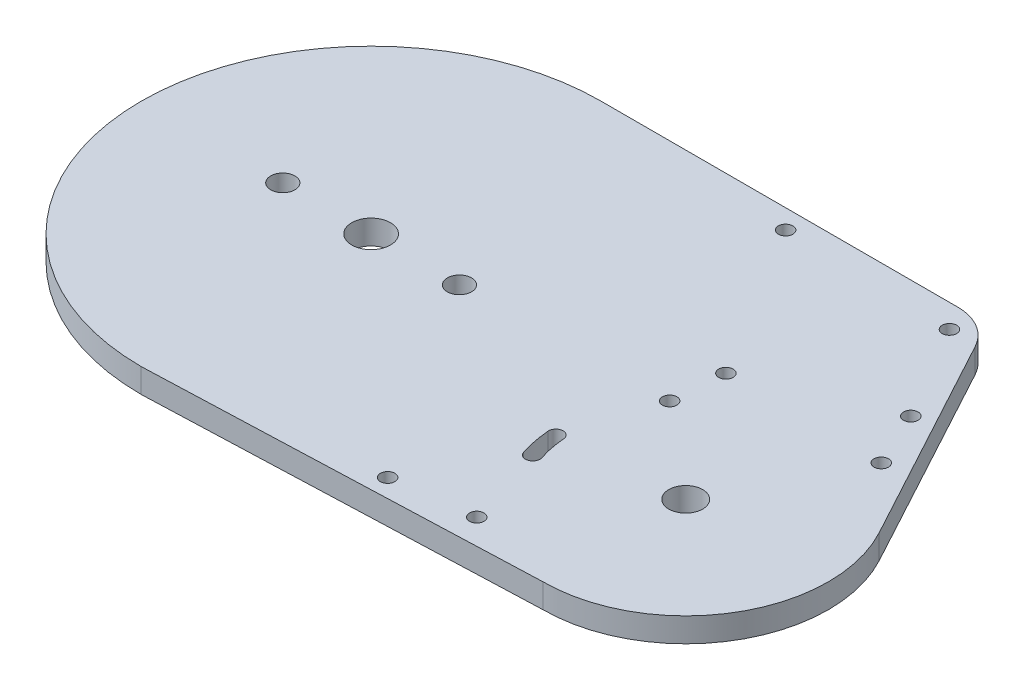
SolidWorks part; units mm, degrees
ref_plane "前视基准面" through (0, 0, 0) normal (0, 0, 1) x (1, 0, 0)
ref_plane "上视基准面" through (0, 0, 0) normal (0, 1, 0) x (1, 0, 0)
ref_plane "右视基准面" through (0, 0, 0) normal (1, 0, 0) x (0, 0, -1)
sketch "Sketch1" plane through (0, 0, 0) normal (0, 1, 0) x (1, 0, 0)
  line L0 (0, 0) -> (0, -15) construction
  line L1 (0, -15) -> (80, -15) construction
  line L2 (0, -47.5) -> (0, -44.5) construction
  line L3 (0, -44.5) -> (94.3585, -44.5) construction
  line L4 (0, -47.5) -> (80, -44.5)
  line L5 (0, 47.5) -> (73.764, 47.5)
  line L6 (82.559, 42.259) -> (105.9453, -0.9611)
  line L7 (0, 0) -> (80, -15) construction
  line L8 (80, -15) -> (60.7426, 0.9422) construction
  line L9 (78.1615, 44.8795) -> (78.8831, 46.0904) construction
  line L10 (78.8831, 46.0904) -> (76.8355, 42.6542) construction
  line L11 (73.764, 47.5) -> (82.559, 42.259) construction
  line L12 (78.1615, 44.8795) -> (73.764, 37.5) construction
  arc A0 (0, 47.5) -> (0, -47.5) centre (0, 0) ccw
  arc A2 (80, -44.5) -> (105.9453, -0.9611) centre (80, -15) ccw
  circle A3 centre (75.0001, 47.5) radius 7.5 construction
  arc A4 (82.559, 42.259) -> (73.764, 47.5) centre (73.764, 37.5) ccw
  circle A5 centre (0, 0) radius 4
  circle A12 centre (80, -15) radius 25 construction
  circle A15 centre (60.7426, 0.9422) radius 1.5
  circle A17 centre (0, 0) radius 18.25 construction
  circle A18 centre (18.25, 0) radius 2.5
  circle A19 centre (-18.25, 0) radius 2.5
  circle A20 centre (80, -15) radius 3.5
  circle A21 centre (76.8355, 42.6542) radius 1.5
  circle A22 centre (88.3547, 23.1429) radius 1.5
  circle A23 centre (42.1373, 43.5) radius 1.5
  circle A24 centre (45.2934, -41.8851) radius 1.5
  circle A25 centre (61.5917, 11.711) radius 1.5
  circle A26 centre (93.688, 11.711) radius 1.5
  circle A27 centre (61.5917, -39.7686) radius 1.5
  arc A29 (56.2754, -22.8831) -> (55.073, -16.9094) centre (80, -15) cw construction
  arc A30 (53.5774, -17.024) -> (54.8519, -23.3561) centre (80, -15) ccw
  arc A31 (56.5686, -16.7949) -> (57.6989, -22.4101) centre (80, -15) ccw
  arc A32 (56.5686, -16.7949) -> (53.5774, -17.024) centre (55.073, -16.9094) ccw
  arc A33 (54.8519, -23.3561) -> (57.6989, -22.4101) centre (56.2754, -22.8831) ccw
  point P28 (75, -15)
  point P46 (55.4915, -19.933)
  dimension "D1" = 95
  dimension "D4" = 29
  dimension "D6" = 15
  dimension "D7" = 10
  dimension "D8" = 8
  dimension "D9" = 50
  dimension "D10" = 3
  dimension "D12" = 4
  dimension "D11" = 36.5
  dimension "D13" = 5
  dimension "D14" = 5
  dimension "D15" = 7
  dimension "D16" = 3
  dimension "D17" = 3
  dimension "D18" = 3
  dimension "D19" = 3
  dimension "D20" = 3
  dimension "D21" = 3
  dimension "D22" = 3
  dimension "D2" = 15
  dimension "D3" = 80
  dimension "D5" = 3
extrude "Boss-Extrude1" add sketch "Sketch1" along normal blind 5
